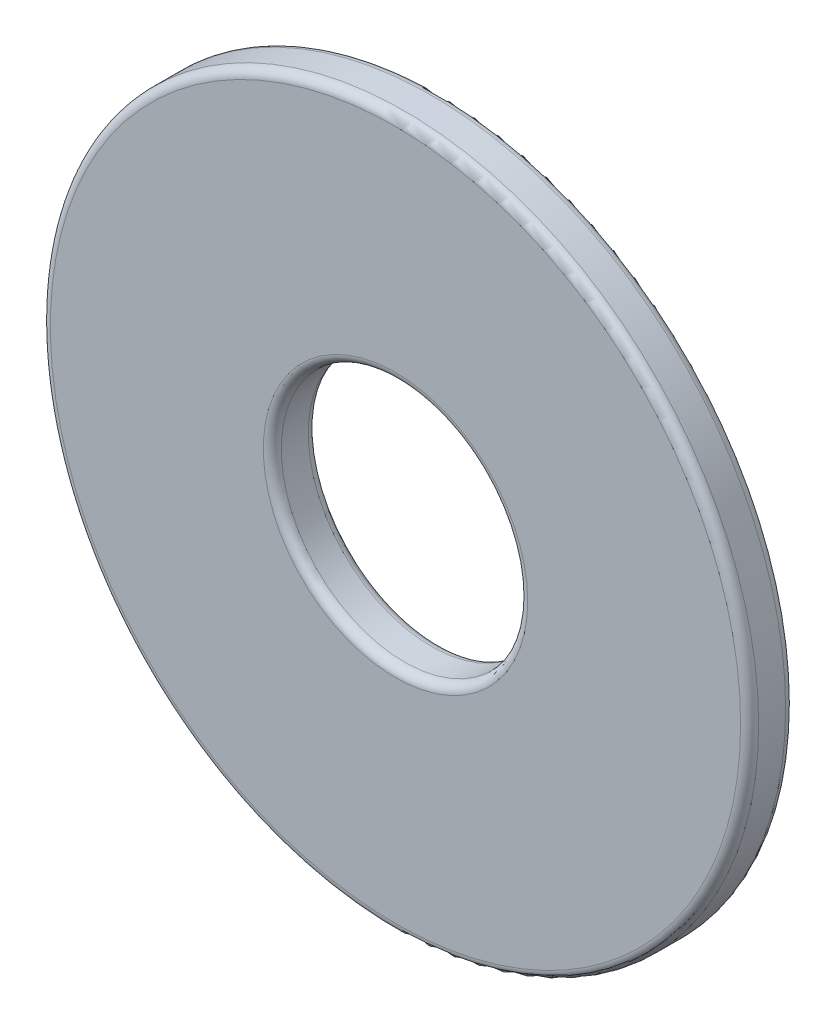
SolidWorks part; units mm, degrees
ref_plane "Front Plane" through (0, 0, 0) normal (0, 0, 1) x (1, 0, 0)
ref_plane "Top Plane" through (0, 0, 0) normal (0, 1, 0) x (1, 0, 0)
ref_plane "Right Plane" through (0, 0, 0) normal (1, 0, 0) x (0, 0, -1)
sketch "Sketch1" plane through (0, 0, 0) normal (0, 0, 1) x (1, 0, 0)
  circle A0 centre (0, 0) radius 4.4196
  circle A1 centre (0, 0) radius 12.7
  point P4 (0, 12.7)
  point P5 (0, 4.4196)
  point P6 (0, -4.4196)
  point P7 (4.4196, 0)
  point P8 (-4.4196, 0)
  dimension "OD" = 25.4
  dimension "ID" = 8.8392
sketch "Sketch2" plane through (0, 0, 0) normal (1, 0, 0) x (0, 0, -1)
  line L1 (-0.8065, 12.7) -> (0.8065, 12.7)
  line L2 (-0.8065, 12.7) -> (-0.8064, -12.7)
  line L3 (-0.8064, -12.7) -> (0.8065, -12.7)
  line L4 (0.8065, 12.7) -> (0.8065, -12.7)
  point P4 (0, 12.7)
  point P5 (0.8065, 0)
  dimension "Thickness" = 1.6129
sketch "Sketch3" plane through (0, 0, 0) normal (0, 0, 1) x (1, 0, 0)
  circle A0 centre (0, 0) radius 4.4196 construction
  circle A1 centre (0, 0) radius 12.7 construction
  circle A2 centre (0, 0) radius 4.4196
  circle A3 centre (0, 0) radius 12.7
extrude "Boss-Extrude1" add sketch "Sketch3" against normal up to vertex (0.8065 mm away) from vertex at 0.8065 starting at point (0, 12.7, 0.8065)
fillet "Fillet1" radius 0.3226 4 edges at (4.4196, 0, 0.8065) (4.4196, 0, -0.8065) (12.7, 0, 0.8065) (12.7, 0, -0.8065)
equation "\"D1@Fillet1\"=\"Thickness@Sketch2\"*.2"
